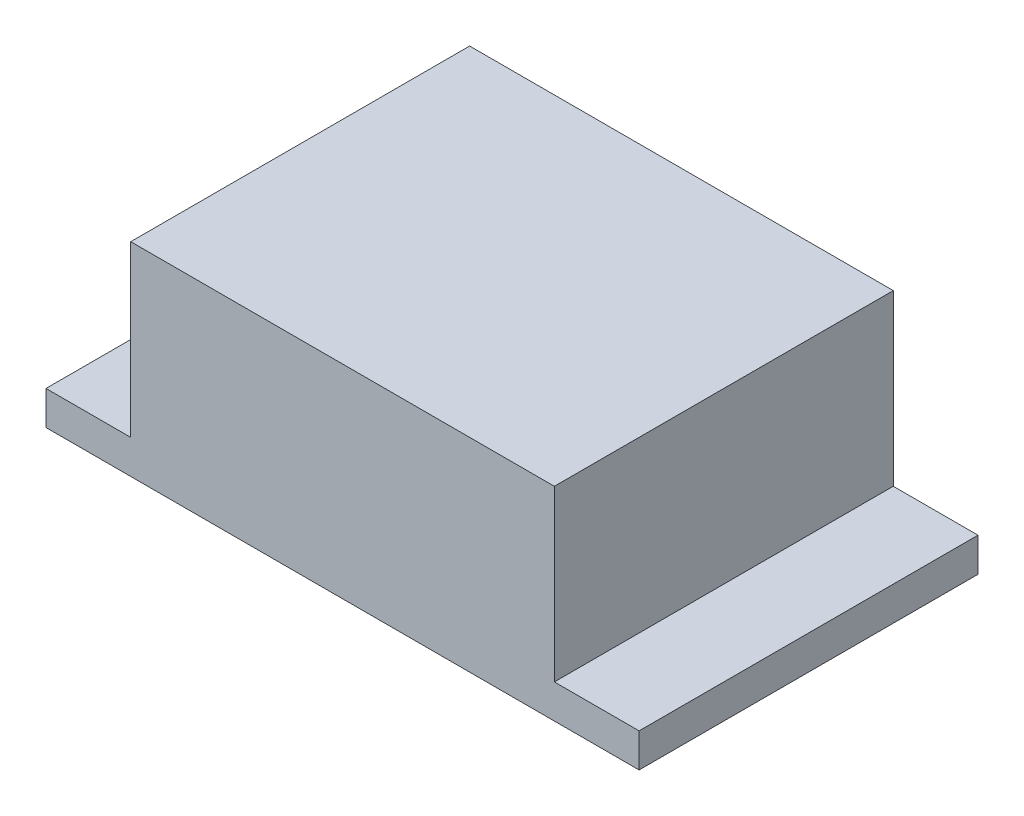
SolidWorks part; units mm, degrees
ref_plane "前视基准面" through (0, 0, 0) normal (0, 0, 1) x (1, 0, 0)
ref_plane "上视基准面" through (0, 0, 0) normal (0, 1, 0) x (1, 0, 0)
ref_plane "右视基准面" through (0, 0, 0) normal (1, 0, 0) x (0, 0, -1)
sketch "草图1" plane through (0, 0, 0) normal (0, 1, 0) x (1, 0, 0)
  line L1 (-17.5, 10) -> (17.5, 10)
  line L2 (-17.5, 10) -> (-17.5, -10)
  line L3 (-17.5, -10) -> (17.5, -10)
  line L4 (17.5, 10) -> (17.5, -10)
  line L5 (-17.5, 10) -> (17.5, -10) construction
  line L6 (-17.5, -10) -> (17.5, 10) construction
  point P0 (0, 0)
  dimension "D1" = 20
  dimension "D2" = 35
extrude "凸台-拉伸1" add sketch "草图1" along normal blind 2
sketch "草图2" plane through (0, 2, 0) normal (0, 1, 0) x (1, 0, 0)
  line L0 (-17.5, -10) -> (17.5, -10) construction
  line L1 (-12.5, 10) -> (12.5, 10)
  line L2 (-12.5, 10) -> (-12.5, -10)
  line L3 (-12.5, -10) -> (12.5, -10)
  line L4 (12.5, 10) -> (12.5, -10)
  line L5 (-12.5, 10) -> (12.5, -10) construction
  line L6 (-12.5, -10) -> (12.5, 10) construction
  point P0 (0, 0)
  dimension "D1" = 25
extrude "凸台-拉伸2" add sketch "草图2" along normal blind 10
